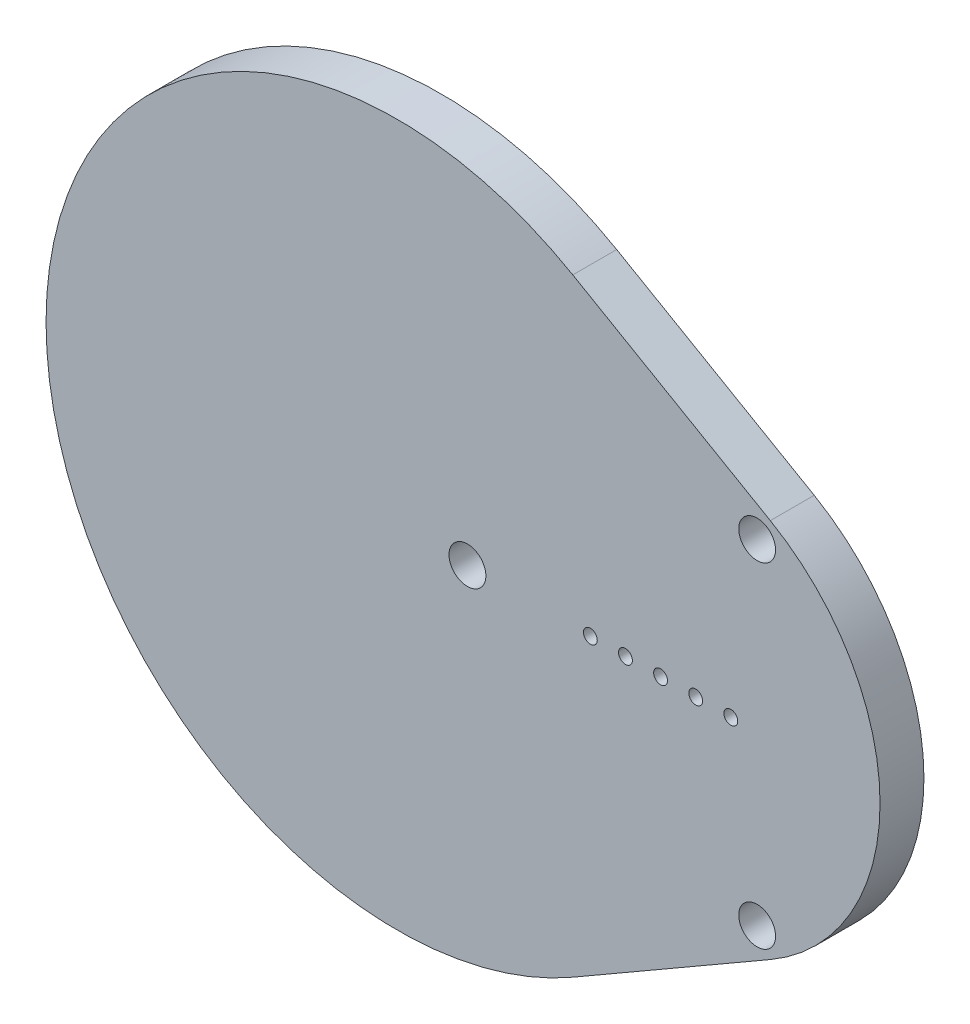
SolidWorks part; units mm, degrees
ref_plane "Front" through (0, 0, 0) normal (0, 0, 1) x (1, 0, 0)
ref_plane "Top" through (0, 0, 0) normal (0, 1, 0) x (1, 0, 0)
ref_plane "Right" through (0, 0, 0) normal (1, 0, 0) x (0, 0, -1)
sketch "Sketch1" plane through (0, 0, 0) normal (0, 0, 1) x (1, 0, 0)
  line L0 (31.75, 0) -> (31.75, -38.4943)
  line L1 (-5.08, 0) -> (-10.16, 0) construction
  line L2 (15.875, 27.4963) -> (-12.7, 43.9941)
  line L3 (15.875, -27.4963) -> (-12.7, -43.9941)
  line L4 (5.08, 0) -> (0, 0) construction
  line L5 (0, 0) -> (-5.08, 0) construction
  line L6 (5.08, 0) -> (10.16, 0) construction
  circle A0 centre (0, 0) radius 12.7 construction
  circle A1 centre (0, 0) radius 31.75
  circle A2 centre (-38.1, 0) radius 50.8
  circle A4 centre (-27.94, 0) radius 2.665
  circle A5 centre (13.97, 24.1967) radius 2.665
  circle A6 centre (13.97, -24.1967) radius 2.665
  circle A8 centre (0, 0) radius 1
  circle A9 centre (-5.08, 0) radius 1
  circle A10 centre (5.08, 0) radius 1
  circle A11 centre (-10.16, 0) radius 1
  circle A12 centre (10.16, 0) radius 1
  point P17 (0, 0)
  dimension "D1" = 25.4
  dimension "D2" = 63.5
  dimension "D3" = 101.6
  dimension "D4" = 27.94
  dimension "D5" = 5.33
  dimension "D7" = 2
  dimension "D8" = 5.08
  dimension "D6" = 3
extrude "Boss-Extrude1" add sketch "Sketch1" along normal blind 6.35 contours A1 A2 | A2 L3 A1 | A2 A1 L2 | A5 | A6 | A4 | A11 | A8 | A10 | A12 | A9
